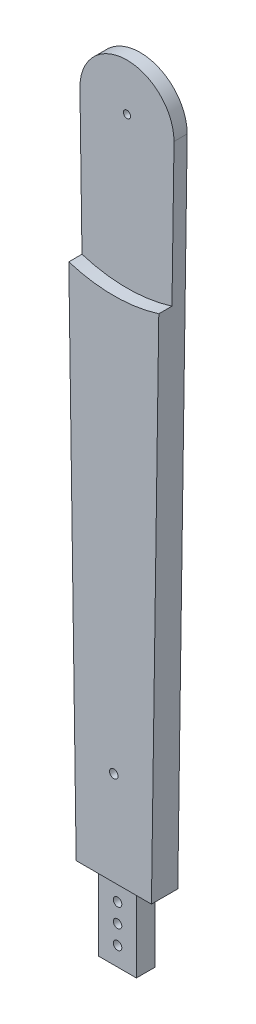
SolidWorks part; units mm, degrees
other "Markup1"
sketch "Sketch21" plane through (-25, -390, 7) normal (-0.035, -0.0156, 0.9993) x (0.9974, 0.0629, 0.0359)
ref_plane "Front Plane" through (0, 0, 0) normal (0, 0, 1) x (1, 0, 0)
ref_plane "Top Plane" through (0, 0, 0) normal (0, 1, 0) x (1, 0, 0)
ref_plane "Right Plane" through (0, 0, 0) normal (1, 0, 0) x (0, 0, -1)
sketch "Sketch7" plane through (0, 0, 0) normal (0, 0, 1) x (1, 0, 0)
  line L0 (-25, 0) -> (-20, -350)
  line L1 (-20, -350) -> (20, -350)
  line L2 (25, 0) -> (20, -350)
  arc A0 (25, 0) -> (-25, 0) centre (0, 0) ccw
  arc A1 (-24.9898, -0.7141) -> (24.9898, -0.7141) centre (0, 0) ccw
  point P9 (0, -350)
  dimension "D2" = 50
  dimension "D1" = 350
  dimension "D3" = 40
extrude "Boss-Extrude3" add sketch "Sketch7" along normal mid plane 14 contours L0 A1 L2 A0 | A1 L0 L1 L2
ref_plane "Plane2" through (0, 0, 0) normal (0, 0, 1) x (1, 0, 0)
sketch "Sketch14" plane through (0, -350, 0) normal (0, -1, 0) x (1, 0, 0)
  line L1 (-10, -5) -> (10, -5)
  line L2 (-10, -5) -> (-10, 5)
  line L3 (-10, 5) -> (10, 5)
  line L4 (10, -5) -> (10, 5)
  line L5 (-10, -5) -> (10, 5) construction
  line L6 (-10, 5) -> (10, -5) construction
  point P0 (0, 0)
  dimension "D1" = 20
  dimension "D2" = 10
sketch "Sketch17" plane through (0, 0, 7) normal (0, 0, 1) x (1, 0, 0)
  circle A0 centre (0, 0) radius 80
  dimension "D1" = 160
extrude "Cut-Extrude9" cut sketch "Sketch17" against normal blind 7
sketch "Sketch18" plane through (0, 0, 7) normal (0, 0, 1) x (1, 0, 0)
  circle A0 centre (0, -300) radius 2.25
  dimension "D1" = 4.5
  dimension "D2" = 300
extrude "Cut-Extrude10" cut sketch "Sketch18" against normal blind 14
sketch "Sketch19" plane through (0, 0, 0) normal (0, 0, 1) x (1, 0, 0)
  circle A0 centre (0, 0) radius 1.9
  dimension "D1" = 3.8
extrude "Cut-Extrude11" cut sketch "Sketch19" against normal blind 7
extrude "Boss-Extrude4" add sketch "Sketch14" along normal blind 40
sketch "Sketch20" plane through (0, 0, 5) normal (0, 0, 1) x (1, 0, 0)
  line L0 (10, -350) -> (-10, -350) construction
  line L1 (10, -390) -> (10, -350) construction
  circle A0 centre (0, -360) radius 2.25
  dimension "D1" = 4.5
  dimension "D2" = 10
  dimension "D3" = 10
extrude "Cut-Extrude12" cut sketch "Sketch20" against normal blind 10
pattern_linear "LPattern1" count 3 spacing 10 along (0, -1, 0) of "Cut-Extrude12"
